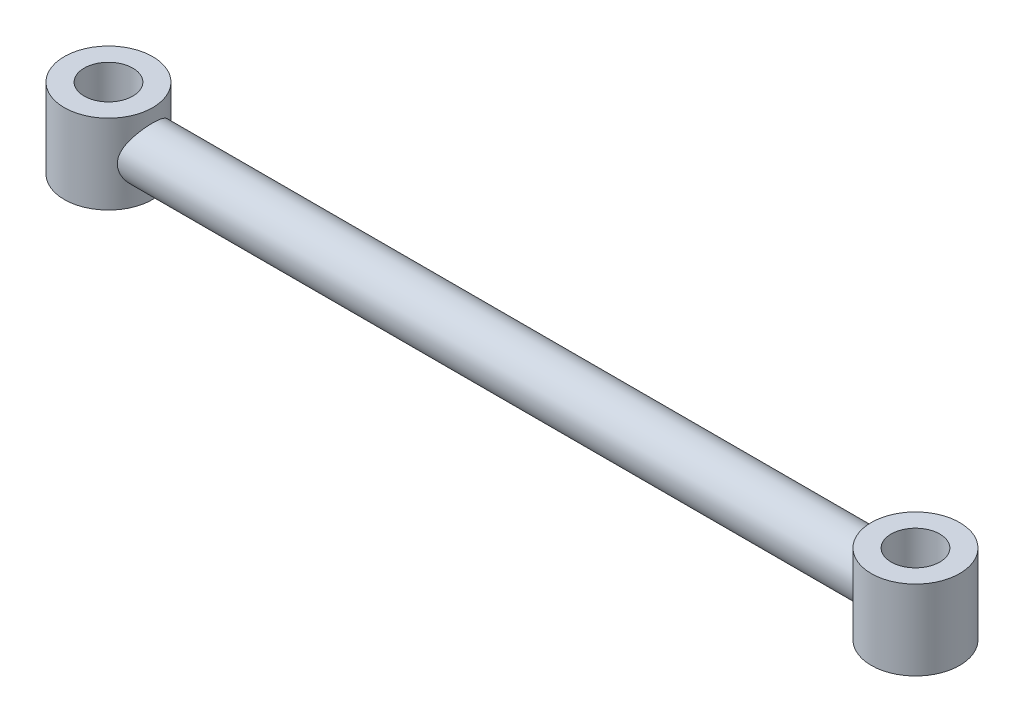
SolidWorks part; units mm, degrees
ref_plane "Front Plane" through (0, 0, 0) normal (0, 0, 1) x (1, 0, 0)
ref_plane "Top Plane" through (0, 0, 0) normal (0, 1, 0) x (1, 0, 0)
ref_plane "Right Plane" through (0, 0, 0) normal (1, 0, 0) x (0, 0, -1)
sketch "Sketch5" plane through (0, 0, 0) normal (1, 0, 0) x (0, 0, -1)
  circle A0 centre (0, 0) radius 12
  dimension "D1" = 24
extrude "Boss-Extrude3" add sketch "Sketch5" along normal mid plane 365
sketch "Sketch2" plane through (0, 0, 0) normal (0, 1, 0) x (1, 0, 0)
  line L0 (182.5, 12) -> (182.5, -12) construction
  line L2 (-182.5, -12) -> (-182.5, 12) construction
  circle A0 centre (182.5, 0) radius 20
  circle A1 centre (-182.5, 0) radius 20
  point P2 (-182.5, 0)
  point P5 (182.5, 0)
  dimension "D1" = 40
extrude "Boss-Extrude4" add sketch "Sketch2" along normal mid plane 36
sketch "Sketch6" plane through (0, -18, 0) normal (0, -1, 0) x (1, 0, 0)
  circle A0 centre (182.5, 0) radius 11
  circle A1 centre (-182.5, 0) radius 11
  dimension "D1" = 22
extrude "Cut-Extrude1" cut sketch "Sketch6" against normal up to surface (36 mm away) up to face at (182.5, 18, 20)
